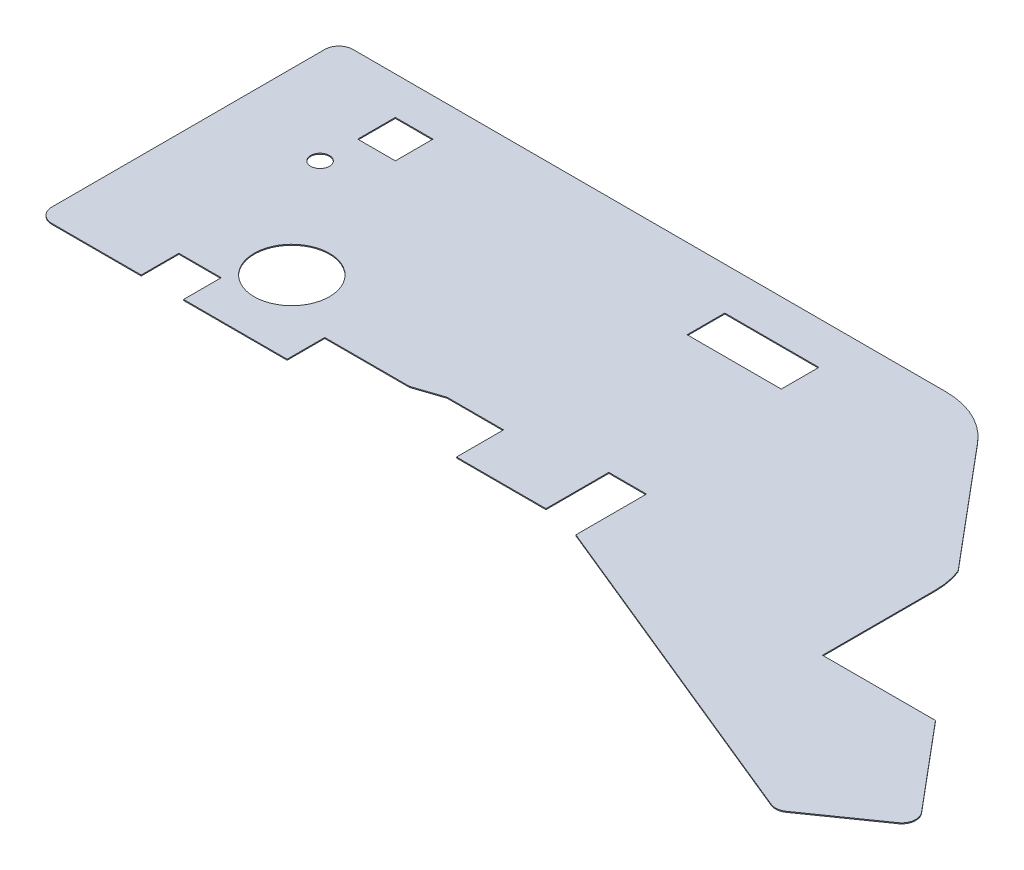
SolidWorks part; units mm, degrees
ref_plane "Front Plane" through (0, 0, 0) normal (0, 0, 1) x (1, 0, 0)
ref_plane "Top Plane" through (0, 0, 0) normal (0, 1, 0) x (1, 0, 0)
ref_plane "Right Plane" through (0, 0, 0) normal (1, 0, 0) x (0, 0, -1)
sketch "Sketch1" plane through (0, 0, 0) normal (0, 1, 0) x (1, 0, 0)
  line L0 (-289.7378, -52.173) -> (-289.7378, 151.027)
  line L1 (-289.7378, 151.027) -> (119.8372, 151.027)
  line L3 (363.9717, -110.8674) -> (306.754, -150.9318)
  line L4 (306.754, -150.9318) -> (65.8622, -52.173)
  line L5 (65.8622, -52.173) -> (-289.7378, -52.173)
  line L6 (159.8867, 132.3517) -> (363.9717, -110.8674)
  arc A0 (119.8372, 151.027) -> (159.8867, 132.3517) centre (119.8372, 98.7462) cw
  point P2 (0, 0)
  dimension "D1" = 203.2
  dimension "D2" = 409.575
  dimension "D3" = 317.5
  dimension "D4" = 355.6
  dimension "D5" = 260.35
  dimension "D6" = 69.85
  dimension "D7" = 85
  dimension "D8" = 130
extrude "Boss-Extrude1" add sketch "Sketch1" along normal blind 0.635
fillet "Fillet1" radius 9.525 4 edges at (-289.7378, 0.3175, 52.173) (-289.7378, 0.3175, -151.027) (306.754, 0.3175, 150.9318) (363.9717, 0.3175, 110.8674)
sketch "Sketch2" plane through (0, 0.635, 0) normal (0, 1, 0) x (1, 0, 0)
  line L0 (357.2901, -102.9046) -> (159.8867, 132.3517) construction
  line L1 (232.1097, 31.668) -> (232.1097, -44.532)
  line L2 (232.1097, -44.532) -> (308.3097, -44.532)
  line L3 (228.6511, 50.4014) -> (308.3097, -44.532)
  line L4 (-121.4628, -52.173) -> (-121.4628, -26.773)
  line L5 (-226.2378, 125.627) -> (-200.8378, 125.627)
  line L6 (-226.2378, 125.627) -> (-226.2378, 100.227)
  line L7 (-226.2378, 100.227) -> (-200.8378, 100.227)
  line L8 (-200.8378, 125.627) -> (-200.8378, 100.227)
  line L9 (-0.8128, 122.452) -> (62.6872, 122.452)
  line L10 (-0.8128, 122.452) -> (-0.8128, 97.052)
  line L11 (-0.8128, 97.052) -> (62.6872, 97.052)
  line L12 (62.6872, 122.452) -> (62.6872, 97.052)
  line L13 (53.1622, -9.7546) -> (78.5622, -9.7546)
  line L14 (53.1622, -9.7546) -> (53.1622, -57.3796)
  line L15 (53.1622, -57.3796) -> (78.5622, -57.3796)
  line L16 (78.5622, -9.7546) -> (78.5622, -57.3796)
  line L17 (-280.2128, -52.173) -> (65.8622, -52.173) construction
  line L18 (-121.4628, -26.773) -> (-64.3128, -26.773)
  line L19 (-64.3128, -26.773) -> (-45.2628, -20.423)
  line L20 (-45.2628, -20.423) -> (-7.1628, -20.423)
  line L21 (-7.1628, -20.423) -> (-7.1628, -52.173)
  line L22 (-7.1628, -52.173) -> (-121.4628, -52.173)
  line L23 (65.8622, -52.173) -> (301.9397, -148.958) construction
  line L24 (119.8372, 151.027) -> (-280.2128, 151.027) construction
  line L25 (-289.7378, 141.502) -> (-289.7378, -42.648) construction
  line L27 (-219.8878, -52.173) -> (-191.3128, -52.173)
  line L28 (-219.8878, -52.173) -> (-219.8878, -26.773)
  line L29 (-219.8878, -26.773) -> (-191.3128, -26.773)
  line L30 (-191.3128, -52.173) -> (-191.3128, -26.773)
  arc A0 (228.6511, 50.4014) -> (232.1097, 31.668) centre (179.6458, 31.668) cw
  circle A1 centre (-169.0878, -1.373) radius 25.4
  circle A2 centre (-226.2378, 74.827) radius 6.35
  point P44 (-46.5966, -20.423)
  dimension "D3" = 50.8
  dimension "D6" = 12.7
  dimension "D22" = 63.5
  dimension "D23" = 120.65
  dimension "D24" = 50.8
  dimension "D25" = 127
  dimension "D1" = 63.5
  dimension "D2" = 25.4
  dimension "D4" = 25.4
  dimension "D5" = 25.4
  dimension "D7" = 76.2
  dimension "D8" = 76.2
  dimension "D9" = 76.2
  dimension "D10" = 19.05
  dimension "D11" = 47.625
  dimension "D12" = 25.4
  dimension "D13" = 12.7
  dimension "D14" = 57.15
  dimension "D15" = 28.575
  dimension "D16" = 63.5
  dimension "D17" = 25.4
  dimension "D18" = 168.275
  dimension "D19" = 28.575
  dimension "D20" = 25.4
  dimension "D21" = 69.85
  dimension "D26" = 25.4
  dimension "D27" = 31.75
  dimension "D28" = 114.3
  dimension "D29" = 57.15
  dimension "D30" = 38.1
extrude "Cut-Extrude1" cut sketch "Sketch2" against normal through all
